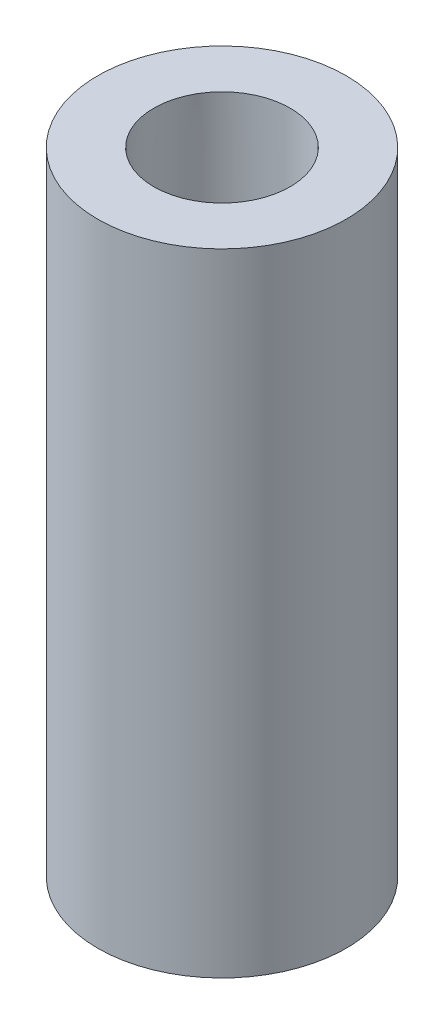
SolidWorks part; units mm, degrees
ref_plane "Plan de face" through (0, 0, 0) normal (0, 0, 1) x (1, 0, 0)
ref_plane "Plan de dessus" through (0, 0, 0) normal (0, 1, 0) x (1, 0, 0)
ref_plane "Plan de droite" through (0, 0, 0) normal (1, 0, 0) x (0, 0, -1)
sketch "Esquisse1" plane through (0, 0, 0) normal (0, 0, 1) x (1, 0, 0)
  line L0 (-2.495, -19.585) -> (-2.495, 0)
  line L1 (-2.495, -15) -> (-2.495, -59) construction
  line L2 (-2.7198, 0) -> (-1.4243, 0) construction
  line L3 (-2.495, 0) -> (-4.1465, 0)
  line L4 (-4.1465, 0) -> (-4, 17.467)
  line L5 (-4, 17.467) -> (-7.2925, 17.467)
  line L6 (-7.2925, 17.467) -> (-7.2925, -19.585)
  line L7 (-7.2925, -19.585) -> (-2.495, -19.585)
  line L8 (0, 0) -> (0, -8.4932) construction
revolve "Révolution1" add sketch "Esquisse1" angle 360 about L8
sketch "Esquisse2" plane through (0, 0, 0) normal (0, 0, 1) x (1, 0, 0)
  circle A0 centre (0, 8.7335) radius 2
  circle A1 centre (0, -9.7925) radius 2
  dimension "D1" = 4
extrude "Enlèv. mat.-Extru.1" cut sketch "Esquisse2" against normal through all
